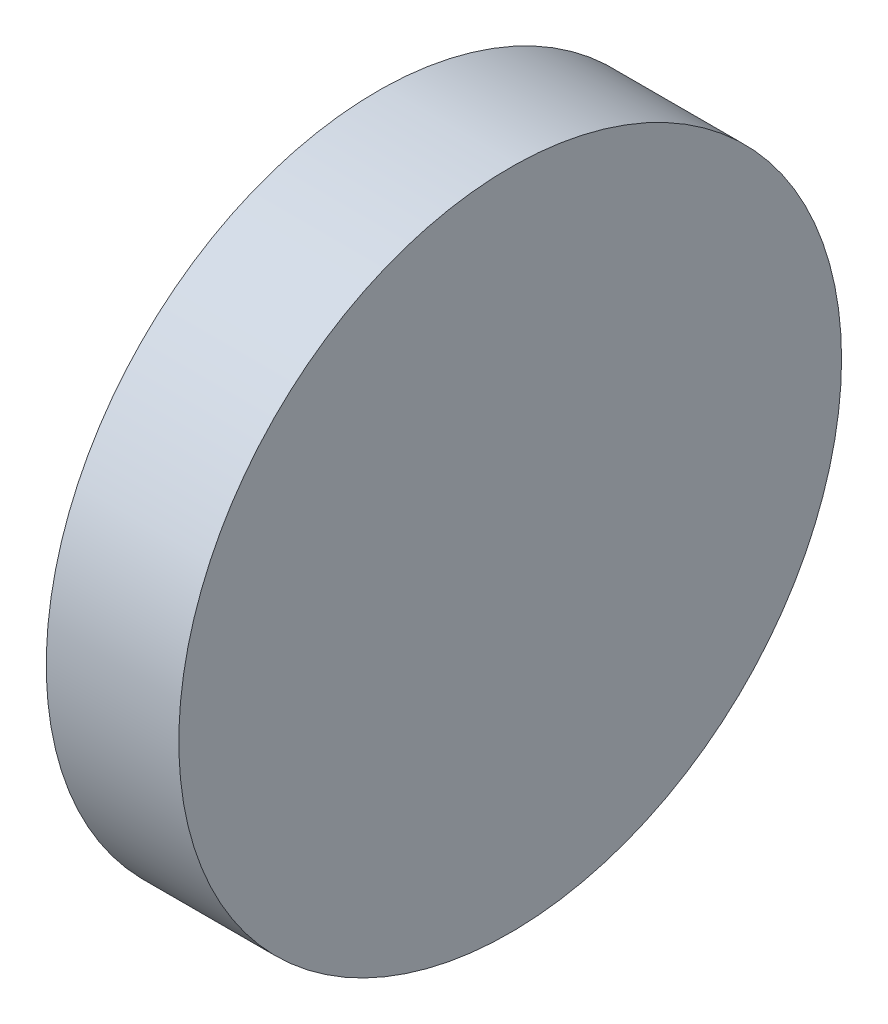
SolidWorks part; units mm, degrees
ref_plane "前视基准面" through (0, 0, 0) normal (0, 0, 1) x (1, 0, 0)
ref_plane "上视基准面" through (0, 0, 0) normal (0, 1, 0) x (1, 0, 0)
ref_plane "右视基准面" through (0, 0, 0) normal (1, 0, 0) x (0, 0, -1)
other "Configuration Table"
sketch "草图1" plane through (0, 0, 0) normal (1, 0, 0) x (0, 0, -1)
  circle A0 centre (0, 0) radius 5
extrude "相机头" add sketch "草图1" along normal blind 2 contours A0
sketch "草图9" plane through (0, 0, 0) normal (-1, 0, 0) x (0, 0, 1)
  circle A0 centre (0, 0) radius 4.4424
extrude "切除-拉伸2" cut sketch "草图9" against normal blind 0.2
sketch "草图10" plane through (0.2, 0, 0) normal (-1, 0, 0) x (0, 0, 1)
  circle A0 centre (0, 0) radius 0.7596
extrude "切除-拉伸3" cut sketch "草图10" against normal blind 0.6
sketch "草图11" plane through (0.8, 0, 0) normal (-1, 0, 0) x (0, 0, 1)
  circle A0 centre (0, 0) radius 0.2781
extrude "切除-拉伸4" cut sketch "草图11" against normal blind 0.6
